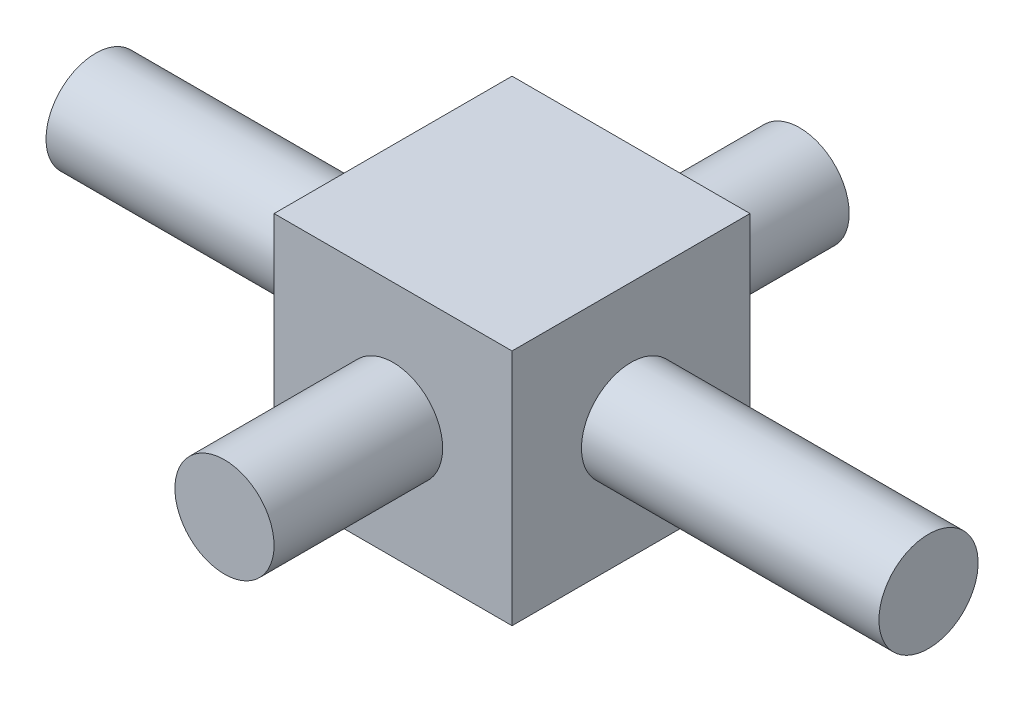
SolidWorks part; units mm, degrees
material "AISI 304"
ref_plane "Alzado" through (0, 0, 0) normal (0, 0, 1) x (1, 0, 0)
ref_plane "Planta" through (0, 0, 0) normal (0, 1, 0) x (1, 0, 0)
ref_plane "Vista lateral" through (0, 0, 0) normal (1, 0, 0) x (0, 0, -1)
ref_plane "Plane2" through (0, 0, -6) normal (0, 0, 1) x (1, 0, 0)
sketch "Sketch1" plane through (0, 0, -6) normal (0, 0, 1) x (1, 0, 0)
  line L0 (-6, -6) -> (6, -6)
  line L1 (6, -6) -> (6, 6)
  line L2 (6, 6) -> (-6, 6)
  line L3 (-6, 6) -> (-6, -6)
extrude "Nucleo" add sketch "Sketch1" along normal blind 12
sketch "Sketch2" plane through (0, 0, 0) normal (0, 0, 1) x (1, 0, 0)
  line L0 (-21, 0) -> (-21, 2.5)
  line L1 (-21, 2.5) -> (21, 2.5)
  line L2 (21, 2.5) -> (21, 0)
  line L3 (21, 0) -> (-21, 0)
  line L4 (-25, 0) -> (25, 0) construction
revolve "Eje_flexion" add sketch "Sketch2" angle 360 about L4
sketch "Sketch3" plane through (0, 0, 0) normal (1, 0, 0) x (0, 0, -1)
  line L0 (-14.5, 0) -> (-14.5, 2.5)
  line L1 (-14.5, 2.5) -> (14.5, 2.5)
  line L2 (14.5, 2.5) -> (14.5, 0)
  line L3 (14.5, 0) -> (-14.5, 0)
  line L4 (-18.5, 0) -> (18.5, 0) construction
revolve "Eje_desviacion" add sketch "Sketch3" angle 360 about L4
